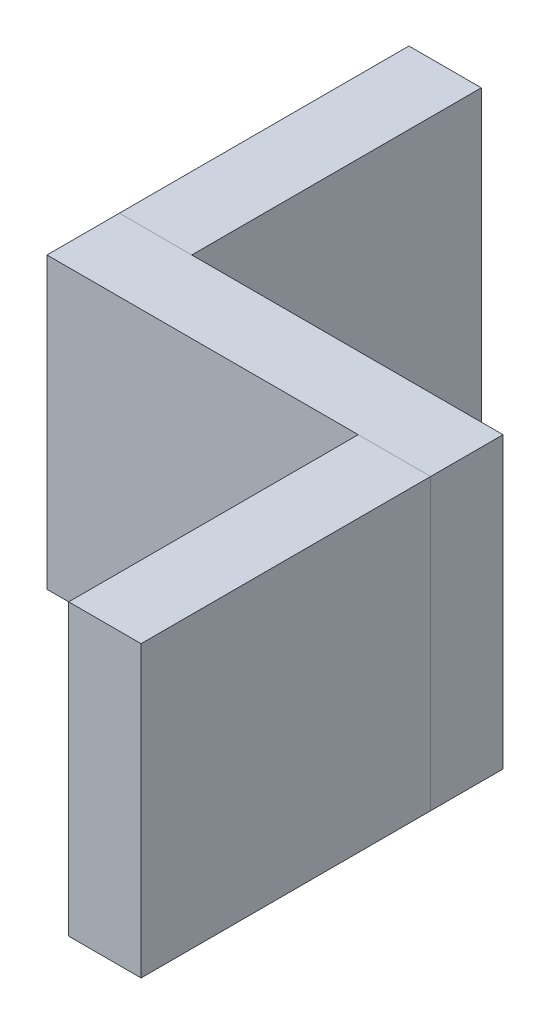
SolidWorks part; units mm, degrees
ref_plane "前视基准面" through (0, 0, 0) normal (0, 0, 1) x (1, 0, 0)
ref_plane "上视基准面" through (0, 0, 0) normal (0, 1, 0) x (1, 0, 0)
ref_plane "右视基准面" through (0, 0, 0) normal (1, 0, 0) x (0, 0, -1)
sketch "草图1" plane through (0, 0, 0) normal (0, 0, 1) x (1, 0, 0)
  line L1 (-26.5, 20) -> (26.5, 20)
  line L2 (-26.5, 20) -> (-26.5, -20)
  line L3 (-26.5, -20) -> (26.5, -20)
  line L4 (26.5, 20) -> (26.5, -20)
  line L5 (-26.5, 20) -> (26.5, -20) construction
  line L6 (-26.5, -20) -> (26.5, 20) construction
  point P0 (0, 0)
  dimension "D1" = 53
  dimension "D2" = 40
extrude "凸台-拉伸1" add sketch "草图1" along normal mid plane 10
sketch "草图2" plane through (0, -20, 0) normal (0, -1, 0) x (1, 0, 0)
  line L1 (-26.5, -5) -> (-16.5, -5)
  line L2 (-26.5, -5) -> (-26.5, -45)
  line L3 (-26.5, -45) -> (-16.5, -45)
  line L4 (-16.5, -5) -> (-16.5, -45)
  line L5 (26.5, 5) -> (16.5, 5)
  line L6 (26.5, 5) -> (26.5, 45)
  line L7 (26.5, 45) -> (16.5, 45)
  line L8 (16.5, 5) -> (16.5, 45)
  dimension "D1" = 10
  dimension "D2" = 10
  dimension "D3" = 40
  dimension "D4" = 40
extrude "凸台-拉伸2" add sketch "草图2" against normal through all separate body
equation "\"零件重量\"= \"SW-质量\""
